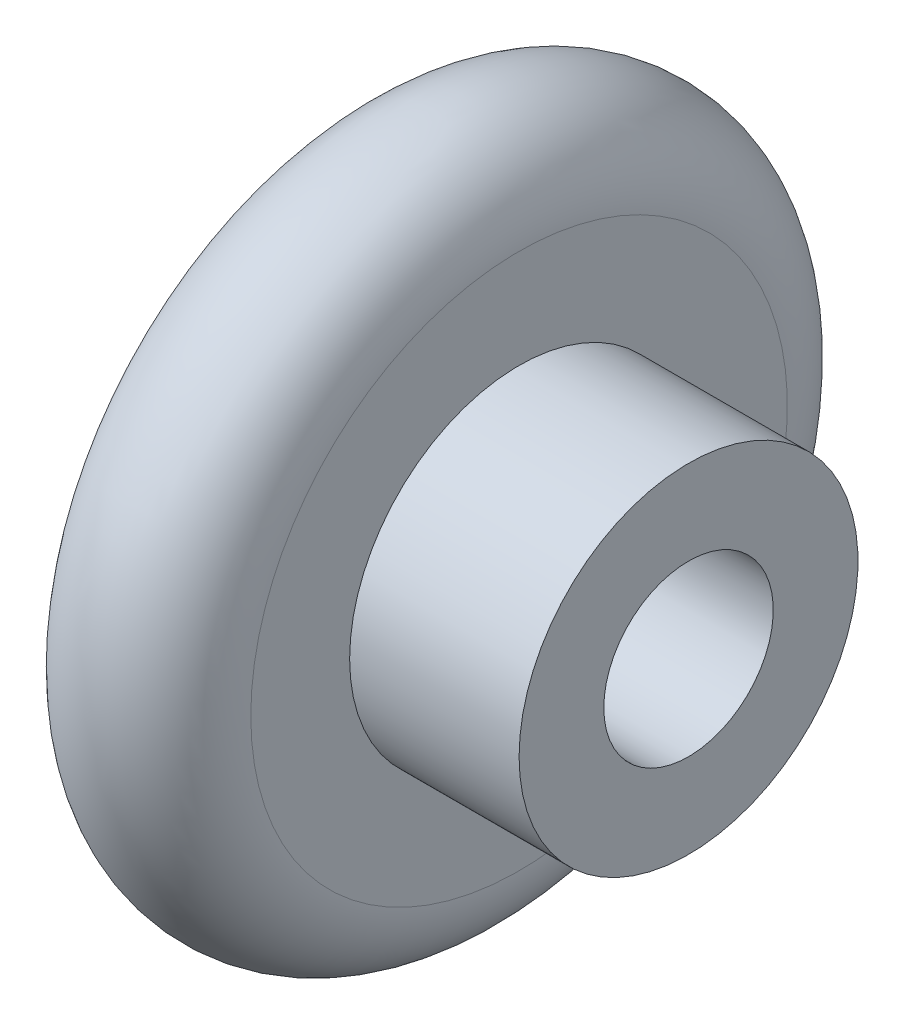
SolidWorks part; units mm, degrees
material "Простая углеродистая сталь"
ref_plane "Спереди" through (0, 0, 0) normal (0, 0, 1) x (1, 0, 0)
ref_plane "Сверху" through (0, 0, 0) normal (0, 1, 0) x (1, 0, 0)
ref_plane "Справа" through (0, 0, 0) normal (1, 0, 0) x (0, 0, -1)
sketch "Эскиз1" plane through (0, 0, 0) normal (0, 0, 1) x (1, 0, 0)
  line L0 (0, 0) -> (59.1931, 0) construction
  line L1 (0, 3) -> (12, 3)
  line L2 (12, 3) -> (12, 6)
  line L3 (12, 6) -> (6, 6)
  line L4 (6, 6) -> (6, 9.5)
  line L5 (0, 9.5) -> (0, 3)
  arc A0 (6, 9.5) -> (0, 9.5) centre (3, 9.5) ccw
  dimension "D3" = 3
  dimension "D4" = 25
  dimension "D1" = 6
  dimension "D2" = 12
  dimension "D5" = 6
revolve "Повернуть1" add sketch "Эскиз1" angle 360 about L0
